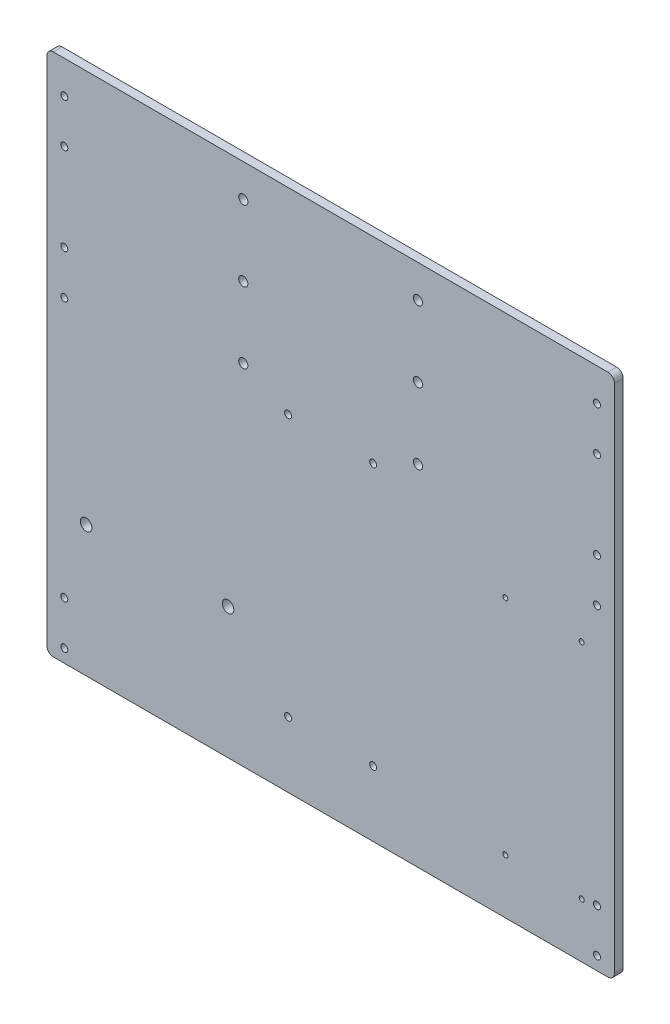
SolidWorks part; units mm, degrees
material "Thornel Mat VMA"
ref_plane "前视基准面" through (0, 0, 0) normal (0, 0, 1) x (1, 0, 0)
ref_plane "上视基准面" through (0, 0, 0) normal (0, 1, 0) x (1, 0, 0)
ref_plane "右视基准面" through (0, 0, 0) normal (1, 0, 0) x (0, 0, -1)
other "Configuration Table"
sketch "草图1" plane through (0, 0, 0) normal (0, 0, 1) x (1, 0, 0)
  line L1 (130, -120) -> (-130, -120)
  line L2 (130, -120) -> (130, 120)
  line L3 (130, 120) -> (-130, 120)
  line L4 (-130, -120) -> (-130, 120)
  line L5 (130, -120) -> (-130, 120) construction
  line L6 (130, 120) -> (-130, -120) construction
  point P0 (0, 0)
  dimension "D1" = 240
  dimension "D2" = 260
extrude "凸台-拉伸1" add sketch "草图1" along normal blind 4
sketch "草图2" plane through (0, 0, 0) normal (0, 0, -1) x (-1, 0, 0)
  line L0 (130, -120) -> (-130, -120) construction
  line L1 (19.5, -90) -> (-19.5, -90) construction
  line L2 (19.5, -90) -> (19.5, 30) construction
  line L3 (19.5, 30) -> (-19.5, 30) construction
  line L4 (-19.5, -90) -> (-19.5, 30) construction
  line L5 (19.5, -90) -> (-19.5, 30) construction
  line L6 (19.5, 30) -> (-19.5, -90) construction
  circle A0 centre (-19.5, 30) radius 1.6
  circle A1 centre (19.5, 30) radius 1.6
  circle A2 centre (19.5, -90) radius 1.6
  circle A3 centre (-19.5, -90) radius 1.6
  point P0 (0, 0)
  dimension "D3" = 3.2
  dimension "D1" = 39
  dimension "D2" = 120
  dimension "D4" = 30
extrude "切除-拉伸1" cut sketch "草图2" against normal blind 63
sketch "草图3" plane through (0, 0, 4) normal (0, 0, 1) x (1, 0, 0)
  line L0 (-130, -44) -> (130, -44) construction
  line L1 (-130, 120) -> (-130, -120) construction
  line L2 (130, -120) -> (130, 120) construction
  line L3 (-130, -120) -> (130, -120) construction
  line L4 (80, 7) -> (115, 7) construction
  line L5 (80, 7) -> (80, -95) construction
  line L6 (80, -95) -> (115, -95) construction
  line L7 (115, 7) -> (115, -95) construction
  line L8 (80, 7) -> (115, -95) construction
  line L9 (80, -95) -> (115, 7) construction
  circle A0 centre (80, 7) radius 1.15
  circle A1 centre (115, 7) radius 1.15
  circle A2 centre (115, -95) radius 1.15
  circle A3 centre (80, -95) radius 1.15
  point P6 (97.5, -44)
  dimension "D3" = 2.3
  dimension "D1" = 35
  dimension "D2" = 102
  dimension "D4" = 15
  dimension "D5" = 25
extrude "切除-拉伸2" cut sketch "草图3" against normal blind 60
fillet "圆角1" radius 3 4 edges at (-130, 120, 2) (130, 120, 2) (130, -120, 2) (-130, -120, 2)
sketch "草图4" plane through (0, 0, 4) normal (0, 0, 1) x (1, 0, 0)
  line L0 (-112, -60) -> (-47, -60) construction
  line L2 (-130, 117) -> (-130, -117) construction
  line L4 (-127, -120) -> (127, -120) construction
  line L5 (-40, 105) -> (-40, 40) construction
  line L8 (127, 120) -> (-127, 120) construction
  line L9 (0, 120) -> (0, 0) construction
  line L10 (40, 105) -> (40, 40) construction
  circle A0 centre (-112, -60) radius 2.65
  circle A1 centre (-47, -60) radius 2.65
  circle A6 centre (-40, 105) radius 2.1
  circle A7 centre (-40, 40) radius 2.1
  circle A8 centre (40, 40) radius 2.1
  circle A9 centre (40, 105) radius 2.1
  circle A10 centre (-40, 72.5) radius 2.1
  circle A11 centre (40, 72.5) radius 2.1
  dimension "D4" = 5.3
  dimension "D5" = 5.3
  dimension "D7" = 4.2
  dimension "D8" = 15
  dimension "D9" = 90
  dimension "D1" = 65
  dimension "D2" = 18
  dimension "D3" = 60
  dimension "D6" = 65
extrude "切除-拉伸3" cut sketch "草图4" against normal blind 10
sketch "草图5" plane through (0, 0, 4) normal (0, 0, 1) x (1, 0, 0)
  line L0 (-122, 120) -> (-122, -120) construction
  line L1 (127, 120) -> (-127, 120) construction
  line L2 (-127, -120) -> (127, -120) construction
  line L3 (-130, 117) -> (-130, -117) construction
  line L4 (0, 120) -> (0, -120) construction
  line L5 (122, 120) -> (122, -120) construction
  circle A0 centre (-122, 105) radius 1.6
  circle A1 centre (-122, 85) radius 1.6
  circle A2 centre (-122, 45) radius 1.6
  circle A3 centre (-122, 25) radius 1.6
  circle A4 centre (-122, -94) radius 1.6
  circle A5 centre (-122, -114) radius 1.6
  circle A6 centre (122, -114) radius 1.6
  circle A7 centre (122, -94) radius 1.6
  circle A8 centre (122, 25) radius 1.6
  circle A9 centre (122, 45) radius 1.6
  circle A10 centre (122, 85) radius 1.6
  circle A11 centre (122, 105) radius 1.6
  dimension "D2" = 3.2
  dimension "D3" = 20
  dimension "D4" = 20
  dimension "D5" = 20
  dimension "D6" = 6
  dimension "D7" = 15
  dimension "D8" = 40
  dimension "D1" = 8
extrude "切除-拉伸4" cut sketch "草图5" against normal blind 10
